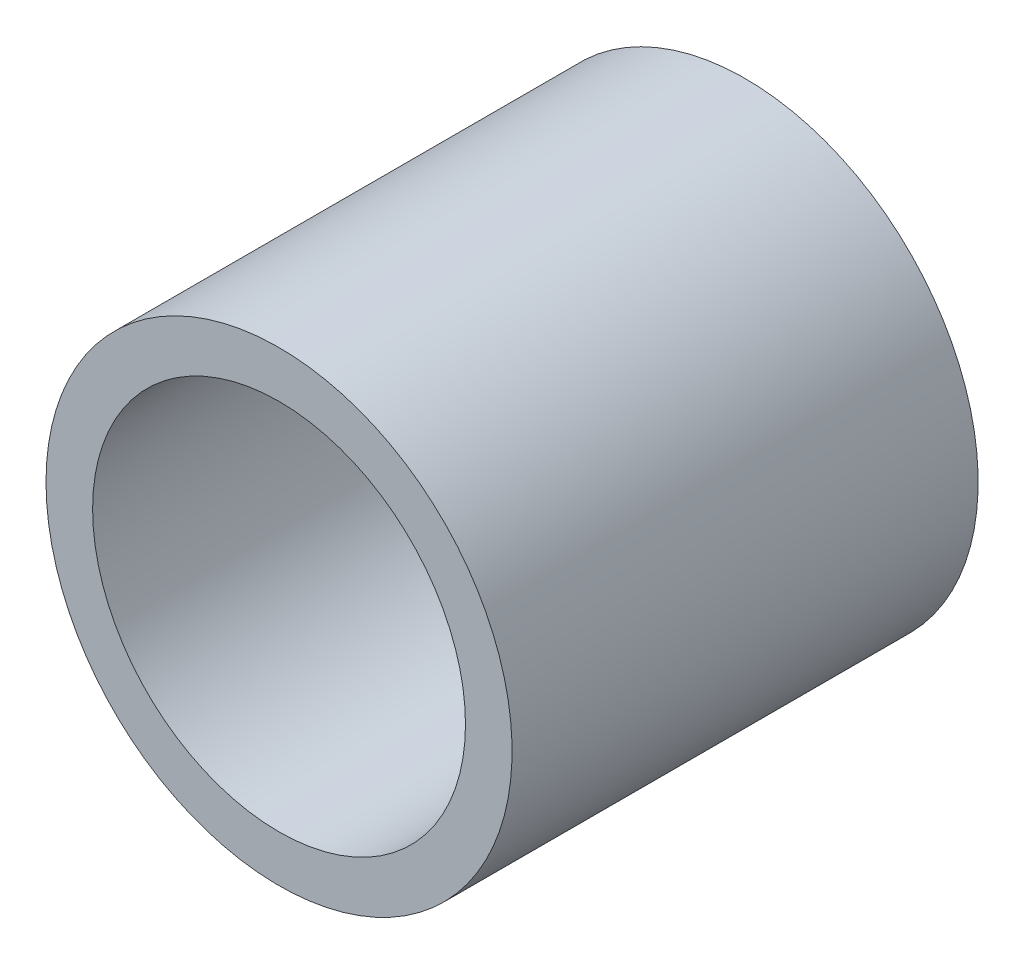
SolidWorks part; units mm, degrees
ref_plane "Ön Düzlem" through (0, 0, 0) normal (0, 0, 1) x (1, 0, 0)
ref_plane "Üst Düzlem" through (0, 0, 0) normal (0, 1, 0) x (1, 0, 0)
ref_plane "Sağ Düzlem" through (0, 0, 0) normal (1, 0, 0) x (0, 0, -1)
sketch "Çizim1" plane through (0, 0, 0) normal (0, 0, 1) x (1, 0, 0)
  circle A0 centre (-10.4384, 10.1046) radius 10
  circle A1 centre (-10.4384, 10.1046) radius 8
  dimension "D1" = 16
  dimension "D2" = 20
extrude "Yükseklik-Ekstrüzyon1" add sketch "Çizim1" along normal blind 20
